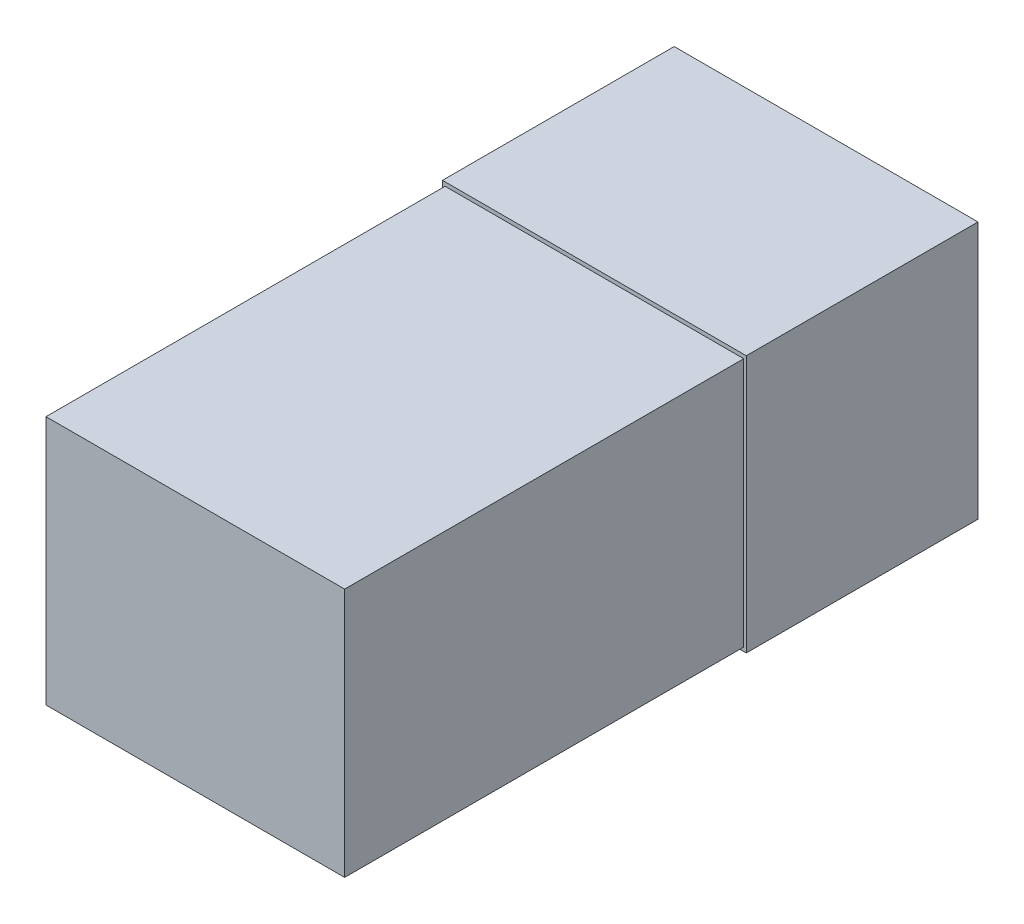
SolidWorks part; units mm, degrees
ref_plane "Alzado" through (0, 0, 0) normal (0, 0, 1) x (1, 0, 0)
ref_plane "Planta" through (0, 0, 0) normal (0, 1, 0) x (1, 0, 0)
ref_plane "Vista lateral" through (0, 0, 0) normal (1, 0, 0) x (0, 0, -1)
sketch "Croquis1" plane through (0, 0, 0) normal (0, 0, 1) x (1, 0, 0)
  line L1 (-5.8, -4.85) -> (5.8, -4.85)
  line L2 (-5.8, -4.85) -> (-5.8, 4.85)
  line L3 (-5.8, 4.85) -> (5.8, 4.85)
  line L4 (5.8, -4.85) -> (5.8, 4.85)
  line L5 (0, 4.85) -> (0, -4.85) construction
  line L6 (-5.8, 0) -> (5.8, 0) construction
  point P0 (0, 0)
  dimension "D1" = 11.6
  dimension "D2" = 9.7
extrude "Saliente-Extruir1" add sketch "Croquis1" along normal blind 15.5
sketch "Croquis2" plane through (0, 0, 0) normal (0, 0, -1) x (-1, 0, 0)
  line L1 (-5.9, -5) -> (5.9, -5)
  line L2 (-5.9, -5) -> (-5.9, 5)
  line L3 (-5.9, 5) -> (5.9, 5)
  line L4 (5.9, -5) -> (5.9, 5)
  line L5 (0, 5) -> (0, -5) construction
  line L6 (-5.9, 0) -> (5.9, 0) construction
  point P0 (0, 0)
  dimension "D1" = 11.8
  dimension "D2" = 10
extrude "Saliente-Extruir2" add sketch "Croquis2" along normal blind 9
